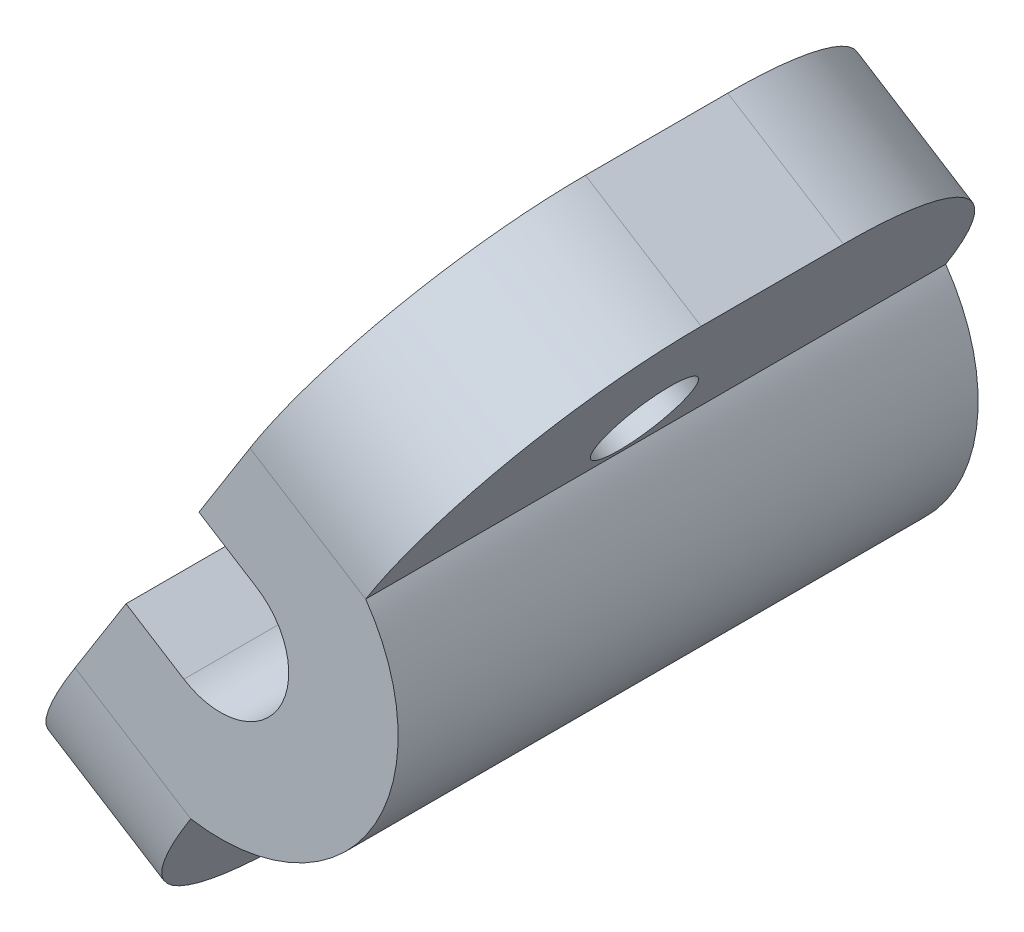
SolidWorks part; units mm, degrees
ref_plane "Front Plane" through (0, 0, 0) normal (0, 0, 1) x (1, 0, 0)
ref_plane "Top Plane" through (0, 0, 0) normal (0, 1, 0) x (1, 0, 0)
ref_plane "Right Plane" through (0, 0, 0) normal (1, 0, 0) x (0, 0, -1)
sketch "Sketch1" plane through (0, 0, 0) normal (0, 0, 1) x (1, 0, 0)
  line L1 (-9.5775, -10.5129) -> (5.347, 13.178)
  line L2 (-9.5775, -10.5129) -> (5.347, 13.178)
  line L3 (-9.5775, -10.5129) -> (5.347, 13.178)
  line L4 (9.5775, 10.5129) -> (-5.347, -13.178)
  line L5 (9.5775, 10.5129) -> (5.347, 13.178)
  line L6 (-5.347, -13.178) -> (-9.5775, -10.5129)
  line L7 (5.347, 13.178) -> (-9.5775, -10.5129)
  line L8 (-0.7827, 3.4478) -> (1.3325, 2.1153)
  line L9 (-3.4478, -0.7827) -> (-1.3325, -2.1153)
  circle A2 centre (0, 0) radius 2.5
  arc A3 (-5.3134, -3.7441) -> (1.0828, 6.4092) centre (0, 0) ccw
  circle A4 centre (0, 0) radius 6.5 construction
  dimension "D6" = 1.0828
  dimension "D3" = 14
  dimension "D4" = 14
  dimension "D5" = 5
  dimension "D1" = 28
  dimension "D2" = 4
extrude "Boss-Extrude2" add sketch "Sketch1" against normal blind 10 contours L4 A3 | L7 A3 L4 A2 L9 | A3 L3 L6 L4 | L4 A3 L7 L8 A2 | A3 L4 L5 L3
sketch "Sketch2" plane through (0, 0, 0) normal (0, 0, 1) x (1, 0, 0)
  line L8 (5.3134, 3.7441) -> (9.5775, 10.5129)
  line L9 (9.5775, 10.5129) -> (5.347, 13.178)
  line L10 (5.347, 13.178) -> (-0.7827, 3.4478)
  line L11 (-0.7827, 3.4478) -> (1.3325, 2.1153)
  line L12 (-1.3325, -2.1153) -> (-3.4478, -0.7827)
  line L13 (-3.4478, -0.7827) -> (-9.5775, -10.5129)
  line L14 (-9.5775, -10.5129) -> (-5.347, -13.178)
  line L15 (-5.347, -13.178) -> (-1.0828, -6.4092)
  line L16 (5.3134, 3.7441) -> (9.5775, 10.5129)
  line L17 (9.5775, 10.5129) -> (5.347, 13.178)
  line L18 (5.347, 13.178) -> (-0.7827, 3.4478)
  line L19 (-0.7827, 3.4478) -> (1.3325, 2.1153)
  line L20 (-1.3325, -2.1153) -> (-3.4478, -0.7827)
  line L21 (-3.4478, -0.7827) -> (-9.5775, -10.5129)
  line L22 (-9.5775, -10.5129) -> (-5.347, -13.178)
  line L23 (-5.347, -13.178) -> (-1.0828, -6.4092)
  arc A2 (-1.0828, -6.4092) -> (5.3134, 3.7441) centre (0, 0) ccw
  arc A3 (-1.3325, -2.1153) -> (1.3325, 2.1153) centre (0, 0) ccw
  arc A4 (-1.0828, -6.4092) -> (5.3134, 3.7441) centre (0, 0) ccw
  arc A5 (-1.3325, -2.1153) -> (1.3325, 2.1153) centre (0, 0) ccw
  dimension "D1" = 0
extrude "Boss-Extrude3" add sketch "Sketch2" along normal blind 8
sketch "Sketch3" plane through (2.1153, -1.3325, 0) normal (0.8461, -0.533, 0) x (0, 0, -1)
  line L0 (10, 14) -> (-8, 14) construction
  circle A2 centre (1.125, 8) radius 1.75
  circle A3 centre (1.125, -8) radius 1.75
  dimension "D1" = 3.5
  dimension "D2" = 8.875
  dimension "D3" = 6
  dimension "D4" = 22
extrude "Cut-Extrude1" cut sketch "Sketch3" against normal up to surface (5 mm away) contours A2 | A3
sketch "Sketch4" plane through (0, 0, -10) normal (0, 0, -1) x (-1, 0, 0)
  line L8 (1.0828, -6.4092) -> (5.347, -13.178)
  line L9 (5.347, -13.178) -> (9.5775, -10.5129)
  line L10 (9.5775, -10.5129) -> (3.4478, -0.7827)
  line L11 (3.4478, -0.7827) -> (1.3325, -2.1153)
  line L12 (-1.3325, 2.1153) -> (0.7827, 3.4478)
  line L13 (0.7827, 3.4478) -> (-5.347, 13.178)
  line L14 (-5.347, 13.178) -> (-9.5775, 10.5129)
  line L15 (-9.5775, 10.5129) -> (-5.3134, 3.7441)
  line L16 (1.0828, -6.4092) -> (5.347, -13.178)
  line L17 (5.347, -13.178) -> (9.5775, -10.5129)
  line L18 (9.5775, -10.5129) -> (3.4478, -0.7827)
  line L19 (3.4478, -0.7827) -> (1.3325, -2.1153)
  line L20 (-1.3325, 2.1153) -> (0.7827, 3.4478)
  line L21 (0.7827, 3.4478) -> (-5.347, 13.178)
  line L22 (-5.347, 13.178) -> (-9.5775, 10.5129)
  line L23 (-9.5775, 10.5129) -> (-5.3134, 3.7441)
  arc A2 (-5.3134, 3.7441) -> (1.0828, -6.4092) centre (0, 0) ccw
  arc A3 (-1.3325, 2.1153) -> (1.3325, -2.1153) centre (0, 0) ccw
  arc A4 (-5.3134, 3.7441) -> (1.0828, -6.4092) centre (0, 0) ccw
  arc A5 (-1.3325, 2.1153) -> (1.3325, -2.1153) centre (0, 0) ccw
  dimension "D1" = 0
extrude "Boss-Extrude4" add sketch "Sketch4" along normal up to surface (3.2043 mm away) contours A4 L16 L17 L18 L19 A5 L20 L21 L22 L23
fillet "Fillet2" radius 8 4 edges at (-7.4622, -11.8455, -13.2043) (-7.4622, -11.8455, 8) (7.4622, 11.8455, 8) (7.4622, 11.8455, -13.2043)
